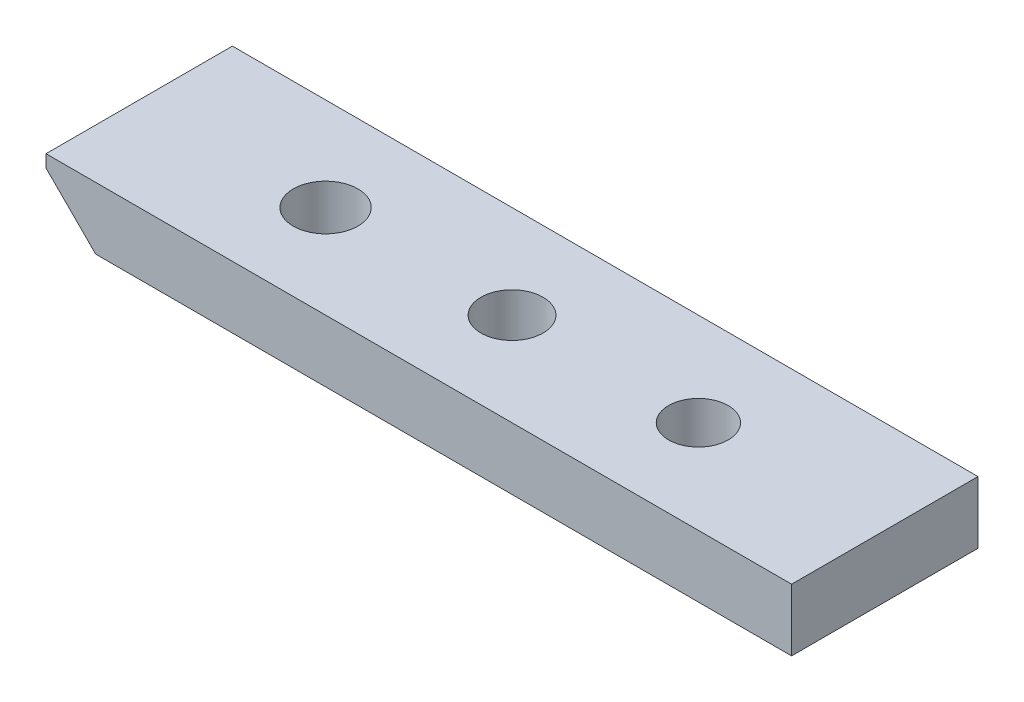
SolidWorks part; units mm, degrees
ref_plane "Front Plane" through (0, 0, 0) normal (0, 0, 1) x (1, 0, 0)
ref_plane "Top Plane" through (0, 0, 0) normal (0, 1, 0) x (1, 0, 0)
ref_plane "Right Plane" through (0, 0, 0) normal (1, 0, 0) x (0, 0, -1)
sketch "Sketch1" plane through (0, 0, 0) normal (0, 1, 0) x (1, 0, 0)
  line L0 (-28.575, 0) -> (-19.05, 0) construction
  line L1 (-28.575, 4.7625) -> (9.525, 4.7625)
  line L2 (-28.575, 4.7625) -> (-28.575, -4.7625)
  line L3 (-28.575, -4.7625) -> (9.525, -4.7625)
  line L4 (9.525, 4.7625) -> (9.525, -4.7625)
  line L5 (-19.05, 0) -> (-9.525, 0) construction
  line L6 (-9.525, 0) -> (0, 0) construction
  line L7 (0, 0) -> (9.525, 0) construction
  point P6 (0, 0)
  point P7 (-19.05, 0)
  point P9 (-9.525, 0)
  point P10 (9.525, 0)
  dimension "D1" = 9.525
  dimension "D2" = 38.1
extrude "Boss-Extrude1" add sketch "Sketch1" along normal blind 3.175
sketch "Sketch2" plane through (0, 0, 0) normal (0, -1, 0) x (1, 0, 0)
  circle A0 centre (-19.05, 0) radius 1.651
  circle A1 centre (-9.525, 0) radius 1.5875
  circle A2 centre (0, 0) radius 1.524
  dimension "D2" = 3.302
  dimension "D3" = 3.175
  dimension "D4" = 3.048
extrude "Cut-Extrude1" cut sketch "Sketch2" against normal through all
chamfer "Chamfer1" distance 2.54 angle 45 1 edges at (-28.575, 0, 0)
